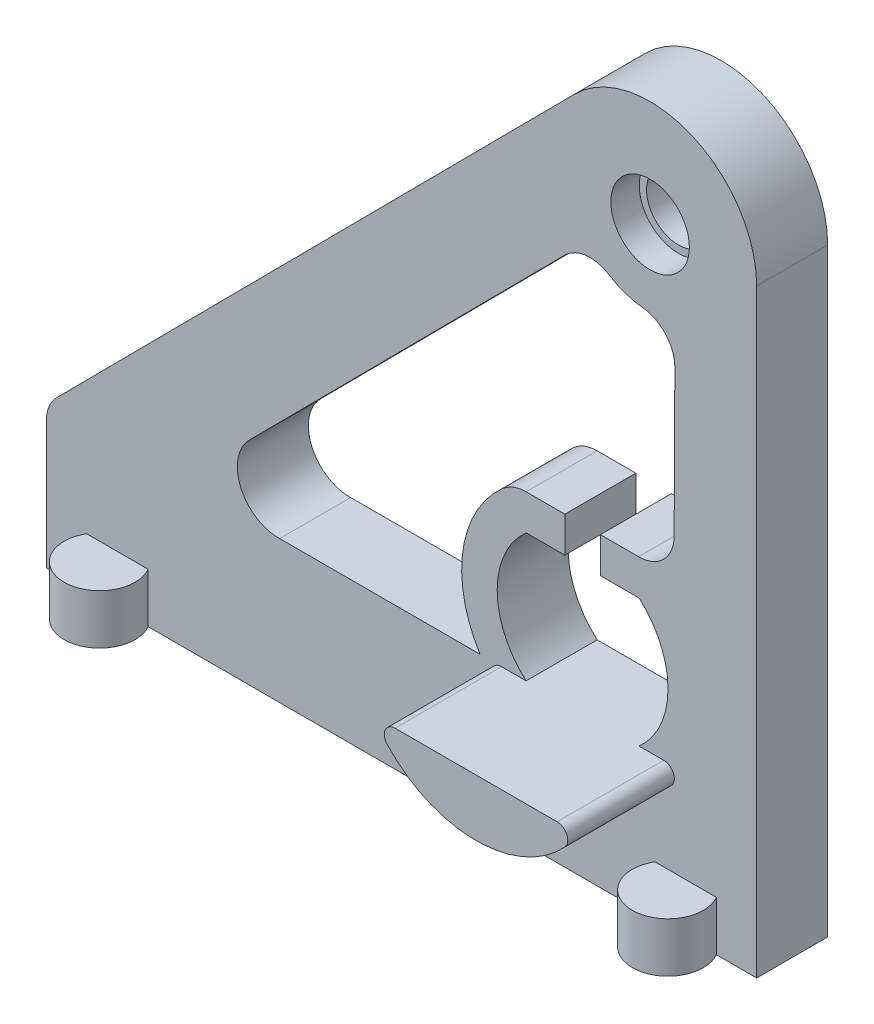
SolidWorks part; units mm, degrees
material "ABS"
ref_plane "Front Plane" through (0, 0, 0) normal (0, 0, 1) x (1, 0, 0)
ref_plane "Top Plane" through (0, 0, 0) normal (0, 1, 0) x (1, 0, 0)
ref_plane "Right Plane" through (0, 0, 0) normal (1, 0, 0) x (0, 0, -1)
sketch "Sketch2" plane through (0, 0, 0) normal (0, 0, 1) x (1, 0, 0)
  line L0 (-88.6256, -17.4255) -> (11.3744, -17.4255)
  line L6 (-88.6256, -17.4255) -> (-88.6256, 0.5271)
  line L7 (11.3744, -17.4255) -> (11.3744, 2.5745)
  line L12 (11.3744, 2.5745) -> (11.3744, 66.9385)
  line L13 (-87.1745, 4.0492) -> (-14.2723, 77.5049)
  line L14 (-15.6294, 20.6245) -> (-21.0761, 20.6245)
  line L17 (-60.0516, 12.4463) -> (-15.6209, 57.2143)
  line L18 (-0.142, 51.3017) -> (-0.2411, 30.6006)
  line L23 (-5.2411, 25.6245) -> (-10.6294, 25.6245)
  line L24 (-5.1827, 20.6245) -> (-10.6294, 20.6245)
  line L25 (-27.5655, 2.5745) -> (-55.7765, 2.5745)
  line L27 (-5.1827, 2.5745) -> (-21.0761, 2.5745)
  line L30 (-10.6294, 25.6245) -> (-10.6294, 20.6245)
  line L32 (-15.6294, 25.6245) -> (-15.6294, 20.6245)
  line L35 (-15.6294, 25.6245) -> (-21.0761, 25.6245)
  arc A10 (11.3744, 66.9385) -> (-14.2723, 77.5049) centre (-3.6256, 66.9385) ccw
  circle A11 centre (-3.6256, 66.9385) radius 5.525
  arc A12 (-9.3838, 57.908) -> (-4.6594, 56.2784) centre (-3.6256, 66.9385) ccw
  arc A13 (-88.6256, 0.5271) -> (-87.1745, 4.0492) centre (-83.6256, 0.5271) cw
  arc A14 (-15.6209, 57.2143) -> (-9.3838, 57.908) centre (-12.072, 53.6921) cw
  arc A15 (-0.142, 51.3017) -> (-4.6594, 56.2784) centre (-5.142, 51.3017) ccw
  arc A17 (-55.7765, 2.5745) -> (-60.0516, 12.4463) centre (-55.9397, 8.3654) cw
  arc A20 (-24.3804, 24.3771) -> (-27.5655, 2.5745) centre (-13.1294, 11.5995) ccw
  arc A21 (-5.2411, 25.6245) -> (-0.2411, 30.6006) centre (-5.2411, 30.6245) ccw
  arc A22 (-21.0761, 25.6245) -> (-24.3804, 24.3771) centre (-21.0761, 20.6245) ccw
  arc A23 (-5.1827, 2.5745) -> (-5.1827, 20.6245) centre (-13.1294, 11.5995) ccw
  arc A24 (-21.0761, 20.6245) -> (-21.0761, 2.5745) centre (-13.1294, 11.5995) ccw
  dimension "D2" = 24.05
  dimension "D3" = 11.05
  dimension "D8" = 5
  dimension "D4" = 5
  dimension "D7" = 5
  dimension "D1" = 100
  dimension "D5" = 18.05
extrude "Boss-Extrude1" add sketch "Sketch2" along normal blind 10
sketch "Sketch4" plane through (0, -17.4255, 0) normal (0, -1, 0) x (1, 0, 0)
  line L1 (-88.6256, 10) -> (11.3744, 10) construction
  line L2 (-88.6256, 0) -> (11.3744, 0) construction
  line L3 (-78.6256, 2.5) -> (-78.6256, 12.5) construction
  line L4 (-88.6256, 10) -> (-88.6256, 0) construction
  circle A0 centre (-78.6256, 12.5) radius 5
  circle A1 centre (-78.6256, 2.5) radius 5
  circle A2 centre (1.3744, 2.5) radius 5
  circle A3 centre (1.3744, 12.5) radius 5
  line M4 (11.3744, 10) -> (-88.6256, 10)
  dimension "D1" = 10
  dimension "D2" = 2.5
  dimension "D3" = 2.5
  dimension "D4" = 10
  dimension "D5" = 10
  dimension "D6" = 2
extrude "Boss-Extrude3" add sketch "Sketch4" against normal blind 7 contours A3 M4 | A0
sketch "Sketch5" plane through (0, 0, 0) normal (0, 0, -1) x (-1, 0, 0)
  circle A0 centre (3.6256, 66.9385) radius 5.525
  circle A1 centre (3.6256, 66.9385) radius 4.5
  dimension "D1" = 9
extrude "Boss-Extrude4" add sketch "Sketch5" against normal blind 6 contours A1
sketch "Sketch6" plane through (0, 0, 10) normal (0, 0, 1) x (1, 0, 0)
  line L0 (-24.5421, 2.5745) -> (-1.7167, 2.5745)
  arc A0 (-25.6448, 0.0576) -> (-0.614, 0.0576) centre (-13.1294, 11.5995) ccw
  arc A1 (-24.3804, 24.3771) -> (-27.5655, 2.5745) centre (-13.1294, 11.5995) ccw construction
  arc A2 (-1.7167, 2.5745) -> (-0.614, 0.0576) centre (-1.7167, 1.0745) cw
  arc A3 (-24.5421, 2.5745) -> (-25.6448, 0.0576) centre (-24.5421, 1.0745) ccw
  point P12 (-27.5655, 2.5745)
  dimension "D1" = 1.5
extrude "Boss-Extrude5" add sketch "Sketch6" along normal blind 15
